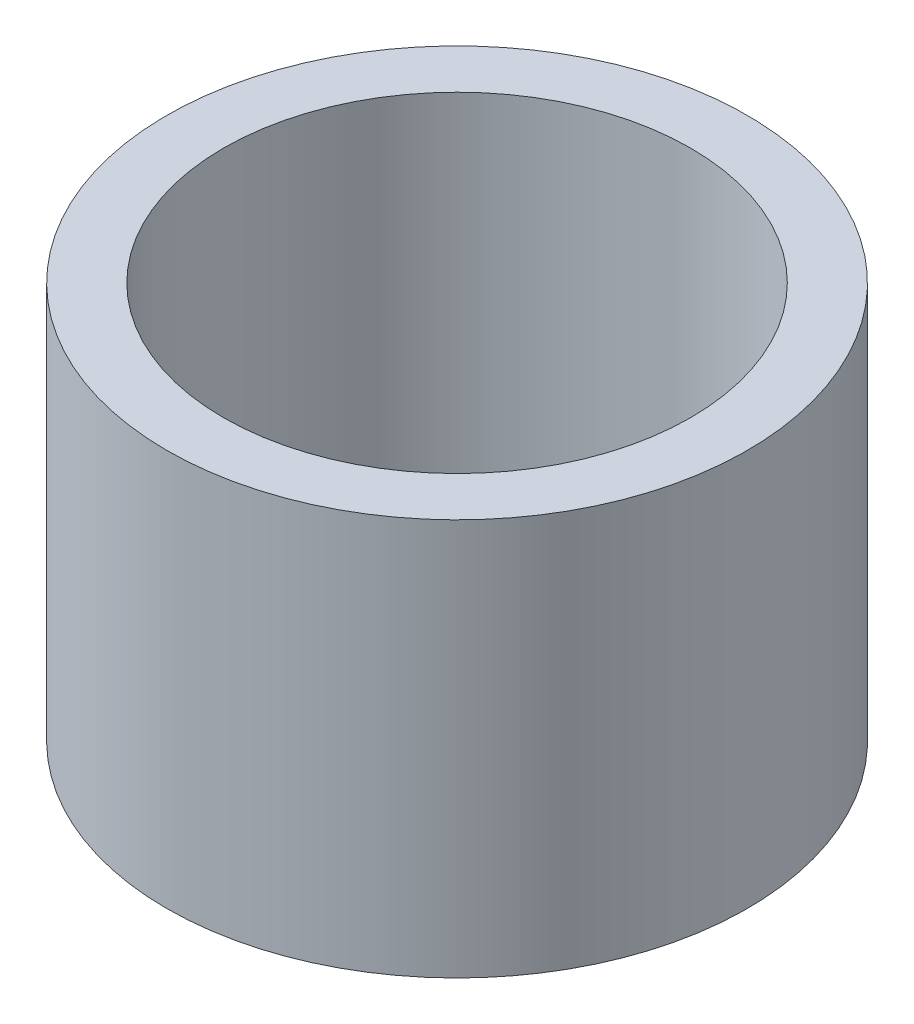
SolidWorks part; units mm, degrees
ref_plane "Front Plane" through (0, 0, 0) normal (0, 0, 1) x (1, 0, 0)
ref_plane "Top Plane" through (0, 0, 0) normal (0, 1, 0) x (1, 0, 0)
ref_plane "Right Plane" through (0, 0, 0) normal (1, 0, 0) x (0, 0, -1)
sketch "Sketch1" plane through (27.2788, 0, -45.5932) normal (0, 1, 0) x (1, 0, 0)
  circle A0 centre (-15.6859, 3.7989) radius 32.512
  dimension "D1" = 65.024
extrude "Boss-Extrude2" add sketch "Sketch1" along normal blind 44.45
sketch "Sketch10" plane through (0, 44.45, 0) normal (0, 1, 0) x (1, 0, 0)
  circle A0 centre (11.593, 49.3921) radius 26.162
  circle A1 centre (11.593, 49.3921) radius 32.512 construction
  dimension "D1" = 52.324
extrude "Cut-Extrude1" cut sketch "Sketch10" against normal blind 44.45 contours A0
